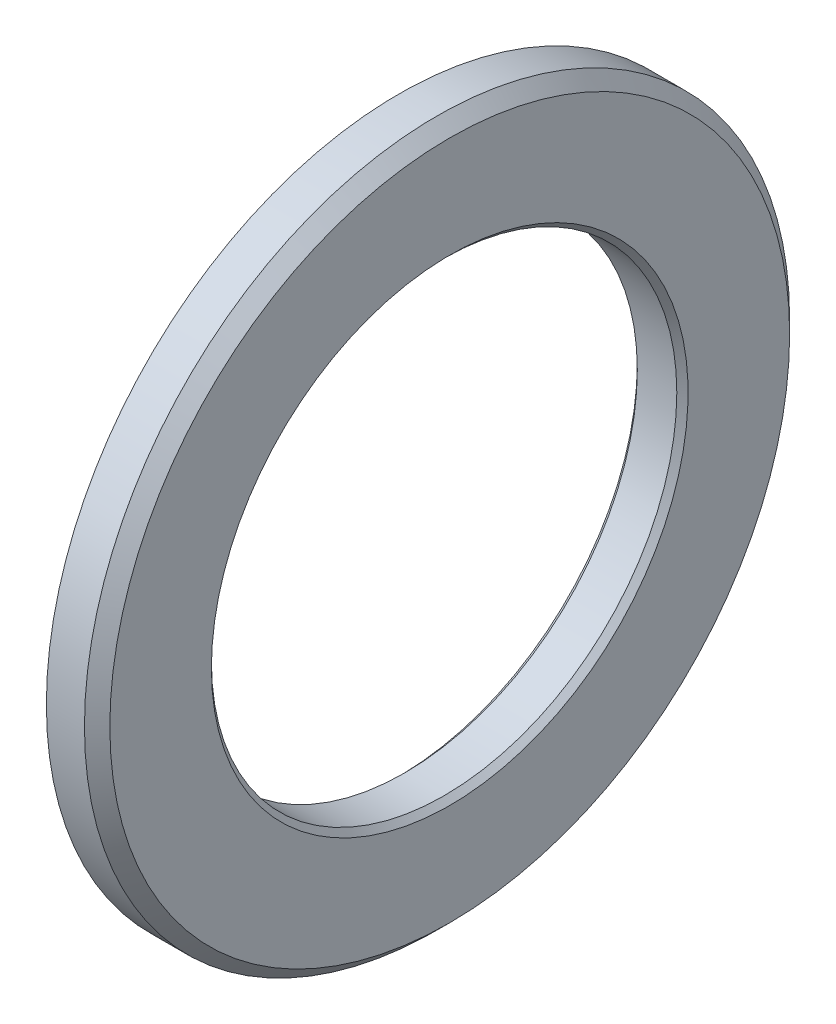
SolidWorks part; units mm, degrees
ref_plane "Plane1" through (0, 0, 0) normal (0, 0, 1) x (1, 0, 0)
ref_plane "Plane2" through (0, 0, 0) normal (0, 1, 0) x (1, 0, 0)
ref_plane "Plane3" through (0, 0, 0) normal (1, 0, 0) x (0, 0, -1)
sketch "Sketch1" plane through (0, 0, 0) normal (0, 0, 1) x (1, 0, 0)
  line L0 (-34.925, 0) -> (9.525, 0) construction
  line L1 (0, 82.5) -> (0, 125)
  line L2 (0, 125) -> (-18, 125)
  line L3 (-18, 125) -> (-18, 82.5)
  line L4 (-18, 82.5) -> (0, 82.5)
  dimension "Thickness" = 18
  dimension "Inside_dia" = 165
  dimension "Outside_dia" = 250
revolve "Base-Revolve" add sketch "Sketch1" angle 360 about L0
chamfer "IDChamfer" distance 2 angle 45 1 edges at (0, 0, 82.5)
chamfer "ODChamfer" distance 4.5 angle 45 1 edges at (0, 0, 125)
chamfer "IDChamferFar" distance 2 angle 45 1 edges at (-18, 0, 82.5)
equation "\"D1@ODChamfer\" =  \"Thickness@Sketch1\" * 0.25"
equation "\"D1@IDChamferFar\" =  \"Chamfer_width@IDChamfer\""
